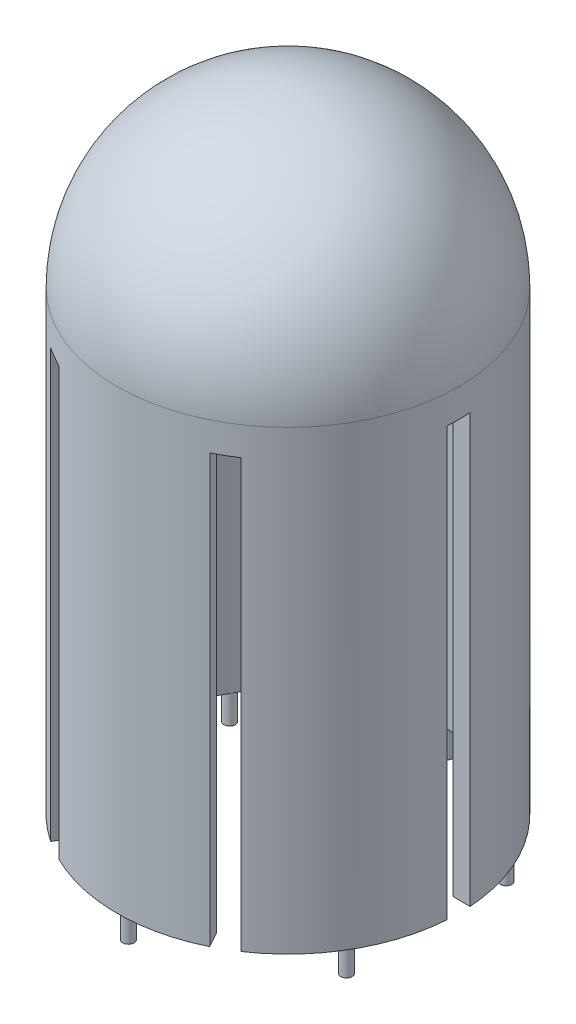
SolidWorks part; units mm, degrees
ref_plane "Front" through (0, 0, 0) normal (0, 0, 1) x (1, 0, 0)
ref_plane "Top" through (0, 0, 0) normal (0, 1, 0) x (1, 0, 0)
ref_plane "Right" through (0, 0, 0) normal (1, 0, 0) x (0, 0, -1)
sketch "Sketch1" plane through (0, 0, 0) normal (0, 1, 0) x (1, 0, 0)
  circle A0 centre (0, 0) radius 38.1
  dimension "D1" = 76.2
extrude "Boss-Extrude1" add sketch "Sketch1" along normal blind 101.6
sketch "Sketch2" plane through (0, 0, 0) normal (1, 0, 0) x (0, 0, -1)
  line L0 (0, 0) -> (0, 139.7) construction
  line L1 (-38.1, 0) -> (38.1, 0) construction
  line L2 (38.1, 101.6) -> (-38.1, 101.6) construction
  line L3 (38.1, 0) -> (38.1, 101.6) construction
  line L4 (38.1, 101.6) -> (34.29, 101.6)
  line L5 (0, 135.89) -> (0, 139.7)
  arc A0 (0, 139.7) -> (38.1, 101.6) centre (0, 101.6) cw
  arc A1 (0, 135.89) -> (34.29, 101.6) centre (0, 101.6) cw
  dimension "D1" = 139.7
  dimension "D2" = 3.81
revolve "Revolve1" add sketch "Sketch2" angle 360 about L0
sketch "Sketch3" plane through (0, 0, 0) normal (0, -1, 0) x (1, 0, 0)
  circle A0 centre (0, 0) radius 34.29
  circle A1 centre (0, 0) radius 38.1 construction
  dimension "D1" = 3.81
extrude "Cut-Extrude2" cut sketch "Sketch3" against normal blind 101.6
sketch "Sketch4" plane through (0, 0, 0) normal (0, 1, 0) x (1, 0, 0)
  line L0 (0, -35.56) -> (0, 0) construction
  circle A0 centre (0, -35.56) radius 1.27
  circle A1 centre (-30.7959, -17.78) radius 1.27
  circle A2 centre (-30.7959, 17.78) radius 1.27
  circle A3 centre (0, 35.56) radius 1.27
  circle A4 centre (30.7959, 17.78) radius 1.27
  circle A5 centre (30.7959, -17.78) radius 1.27
  point P16 (0, 0)
  dimension "D1" = 2.54
  dimension "D2" = 35.56
  dimension "D3" = 6
extrude "Boss-Extrude2" add sketch "Sketch4" against normal blind 6.35
sketch "Sketch5" plane through (0, 0, 0) normal (0, -1, 0) x (1, 0, 0)
  line L0 (-30.7959, 17.78) -> (-17.8673, 30.9471) construction
  line L1 (-21.5633, 32.1967) -> (-17.1952, 34.7903)
  line L2 (-21.5633, 32.1967) -> (-18.5394, 27.1039)
  line L3 (-18.5394, 27.1039) -> (-14.1714, 29.6975)
  line L4 (-17.1952, 34.7903) -> (-14.1714, 29.6975)
  line L5 (-21.5633, 32.1967) -> (-14.1714, 29.6975) construction
  line L6 (-18.5394, 27.1039) -> (-17.1952, 34.7903) construction
  line L7 (-17.8673, 30.9471) -> (0, 35.56) construction
  line L8 (14.203, 29.6076) -> (18.6331, 27.1215)
  line L9 (21.5316, 32.2866) -> (18.6331, 27.1215)
  line L10 (17.1015, 34.7727) -> (21.5316, 32.2866)
  line L11 (17.1015, 34.7727) -> (14.203, 29.6076)
  line L12 (32.7424, 2.5036) -> (32.8045, -2.576)
  line L13 (38.7269, -2.5036) -> (32.8045, -2.576)
  line L14 (38.6648, 2.576) -> (38.7269, -2.5036)
  line L15 (38.6648, 2.576) -> (32.7424, 2.5036)
  line L16 (18.5394, -27.1039) -> (14.1714, -29.6975)
  line L17 (17.1952, -34.7903) -> (14.1714, -29.6975)
  line L18 (21.5633, -32.1967) -> (17.1952, -34.7903)
  line L19 (21.5633, -32.1967) -> (18.5394, -27.1039)
  line L20 (-14.203, -29.6076) -> (-18.6331, -27.1215)
  line L21 (-21.5316, -32.2866) -> (-18.6331, -27.1215)
  line L22 (-17.1015, -34.7727) -> (-21.5316, -32.2866)
  line L23 (-17.1015, -34.7727) -> (-14.203, -29.6076)
  line L24 (-32.7424, -2.5036) -> (-32.8045, 2.576)
  line L25 (-38.7269, 2.5036) -> (-32.8045, 2.576)
  line L26 (-38.6648, -2.576) -> (-38.7269, 2.5036)
  line L27 (-38.6648, -2.576) -> (-32.7424, -2.5036)
  point P0 (-17.8673, 30.9471)
  point P35 (0, 0)
  dimension "D1" = 5.08
  dimension "D3" = 90
  dimension "D2" = 6
extrude "Cut-Extrude5" cut sketch "Sketch5" against normal blind 95.25
sketch "Sketch6" plane through (0, 0, 0) normal (0, 1, 0) x (1, 0, 0)
  line L0 (0, 0) -> (-30.7959, -17.78) construction
